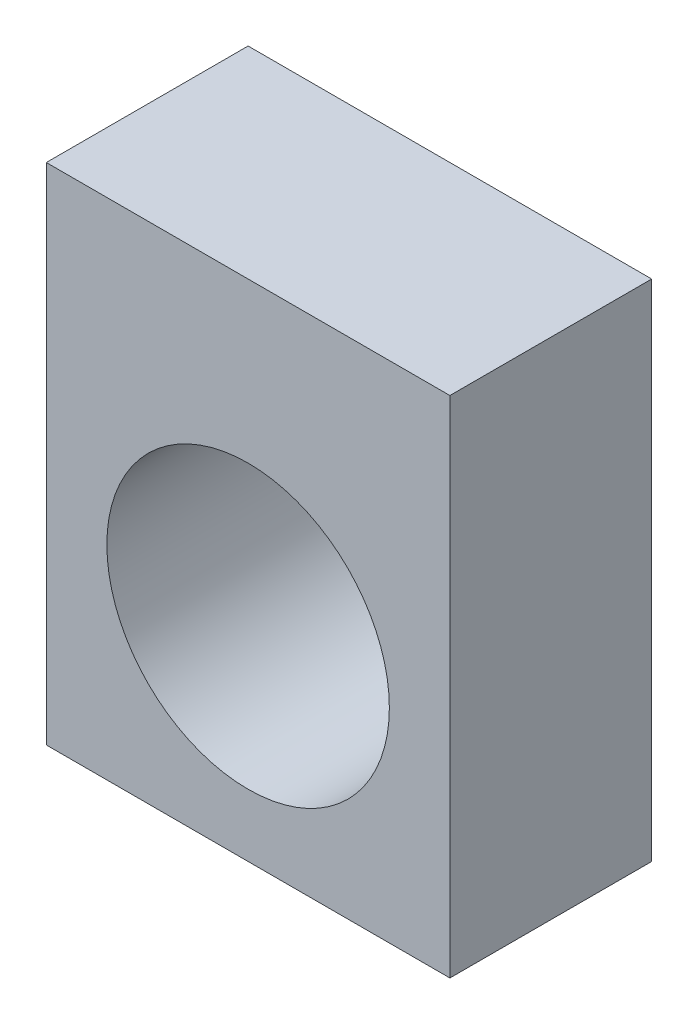
SolidWorks part; units mm, degrees
ref_plane "Plan de face" through (0, 0, 0) normal (0, 0, 1) x (1, 0, 0)
ref_plane "Plan de dessus" through (0, 0, 0) normal (0, 1, 0) x (1, 0, 0)
ref_plane "Plan de droite" through (0, 0, 0) normal (1, 0, 0) x (0, 0, -1)
sketch "Esquisse1" plane through (0, 0, 0) normal (0, 0, 1) x (1, 0, 0)
  line L1 (0, 0) -> (20, 0)
  line L2 (0, 0) -> (0, 25)
  line L3 (0, 25) -> (20, 25)
  line L4 (20, 0) -> (20, 25)
  dimension "D1" = 20
  dimension "D2" = 25
extrude "Boss.-Extru.1" add sketch "Esquisse1" along normal blind 10
sketch "Esquisse2" plane through (0, 0, 10) normal (0, 0, 1) x (1, 0, 0)
  line L0 (10, 0) -> (10, 30.8533) construction
  line L1 (0, 0) -> (20, 0) construction
  line L2 (0, 10.1) -> (21.2157, 10.1) construction
  line L5 (0, 25) -> (0, 0) construction
  circle A0 centre (10, 10.1) radius 7
  dimension "D2" = 14
  dimension "D1" = 10.1
extrude "Enlèv. mat.-Extru.1" cut sketch "Esquisse2" against normal through all
